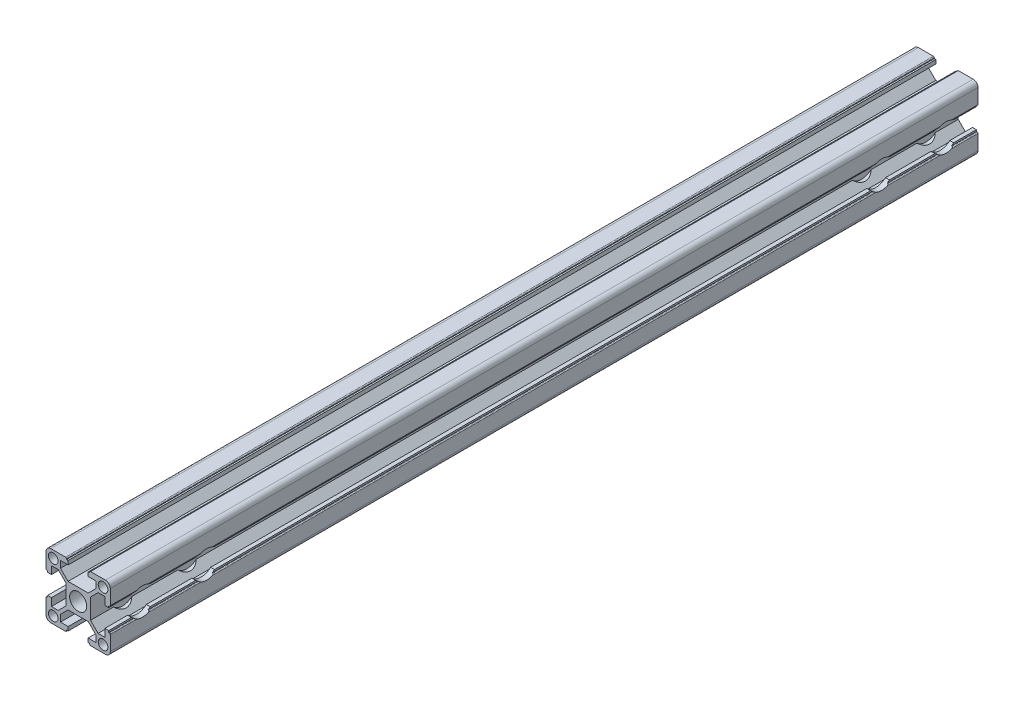
SolidWorks part; units mm, degrees
ref_plane "前视基准面" through (0, 0, 0) normal (0, 0, 1) x (1, 0, 0)
ref_plane "上视基准面" through (0, 0, 0) normal (0, 1, 0) x (1, 0, 0)
ref_plane "右视基准面" through (0, 0, 0) normal (1, 0, 0) x (0, 0, -1)
sketch "草图1" plane through (0, 0, 0) normal (0, 0, 1) x (1, 0, 0)
  line L0 (-7.75, 0) -> (0, 0) construction
  line L1 (7.75, -7.75) -> (-7.75, -7.75) construction
  line L2 (7.75, -7.75) -> (7.75, 7.75) construction
  line L3 (7.75, 7.75) -> (-7.75, 7.75) construction
  line L4 (-7.75, -7.75) -> (-7.75, 7.75) construction
  line L5 (7.75, -7.75) -> (-7.75, 7.75) construction
  line L6 (7.75, 7.75) -> (-7.75, -7.75) construction
  line L7 (0, 0) -> (0, 7.75) construction
  line L8 (3.1429, 3.85) -> (-3.1429, 3.85)
  line L9 (-3.1429, 3.85) -> (-5.5, 6.2071)
  line L10 (-5.5, 6.2071) -> (-5.5, 8.3)
  line L11 (-5.5, 8.3) -> (-3.1, 8.3)
  line L12 (-3.1, 8.3) -> (-3.1, 9.5)
  line L13 (-3.1, 9.5) -> (-3.6, 9.5)
  line L14 (-3.6, 9.5) -> (-3.6, 9.7)
  line L15 (-3.9, 10) -> (-8.5, 10)
  line L16 (-3.85, -3.1429) -> (-3.85, 3.1429)
  line L17 (-3.85, 3.1429) -> (-6.2071, 5.5)
  line L18 (-6.2071, 5.5) -> (-8.3, 5.5)
  line L19 (-8.3, 5.5) -> (-8.3, 3.1)
  line L20 (-9.5, 3.1) -> (-9.5, 3.6)
  line L21 (-8.3, 3.1) -> (-9.5, 3.1)
  line L22 (-9.5, 3.6) -> (-9.7, 3.6)
  line L23 (-10, 3.9) -> (-10, 8.5)
  line L24 (5.5, 8.3) -> (3.1, 8.3)
  line L25 (3.6, 9.5) -> (3.6, 9.7)
  line L26 (3.1, 9.5) -> (3.6, 9.5)
  line L27 (3.1, 8.3) -> (3.1, 9.5)
  line L28 (5.5, 6.2071) -> (5.5, 8.3)
  line L29 (3.1429, 3.85) -> (5.5, 6.2071)
  line L30 (3.85, -3.1429) -> (3.85, 3.1429)
  line L31 (3.85, 3.1429) -> (6.2071, 5.5)
  line L32 (9.5, 3.6) -> (9.7, 3.6)
  line L33 (8.3, 3.1) -> (9.5, 3.1)
  line L34 (9.5, 3.1) -> (9.5, 3.6)
  line L35 (8.3, 5.5) -> (8.3, 3.1)
  line L36 (6.2071, 5.5) -> (8.3, 5.5)
  line L37 (10, 3.9) -> (10, 8.5)
  line L38 (3.9, 10) -> (8.5, 10)
  line L39 (-9.5, -3.6) -> (-9.7, -3.6)
  line L40 (-8.3, -3.1) -> (-9.5, -3.1)
  line L41 (-9.5, -3.1) -> (-9.5, -3.6)
  line L42 (-8.3, -5.5) -> (-8.3, -3.1)
  line L43 (-6.2071, -5.5) -> (-8.3, -5.5)
  line L44 (-3.85, -3.1429) -> (-6.2071, -5.5)
  line L45 (-3.1429, -3.85) -> (-5.5, -6.2071)
  line L46 (-5.5, -6.2071) -> (-5.5, -8.3)
  line L47 (-3.6, -9.5) -> (-3.6, -9.7)
  line L48 (-3.1, -9.5) -> (-3.6, -9.5)
  line L49 (-3.1, -8.3) -> (-3.1, -9.5)
  line L50 (-5.5, -8.3) -> (-3.1, -8.3)
  line L51 (5.5, -6.2071) -> (5.5, -8.3)
  line L52 (3.1, -8.3) -> (3.1, -9.5)
  line L53 (3.1, -9.5) -> (3.6, -9.5)
  line L54 (3.6, -9.5) -> (3.6, -9.7)
  line L55 (5.5, -8.3) -> (3.1, -8.3)
  line L56 (3.1429, -3.85) -> (5.5, -6.2071)
  line L57 (3.1429, -3.85) -> (-3.1429, -3.85)
  line L58 (3.85, -3.1429) -> (6.2071, -5.5)
  line L59 (6.2071, -5.5) -> (8.3, -5.5)
  line L60 (8.3, -5.5) -> (8.3, -3.1)
  line L61 (9.5, -3.1) -> (9.5, -3.6)
  line L62 (8.3, -3.1) -> (9.5, -3.1)
  line L63 (9.5, -3.6) -> (9.7, -3.6)
  line L64 (3.9, -10) -> (8.5, -10)
  line L65 (10, -3.9) -> (10, -8.5)
  line L66 (-10, -3.9) -> (-10, -8.5)
  line L67 (-3.9, -10) -> (-8.5, -10)
  circle A0 centre (0, 0) radius 2.65
  circle A1 centre (-7.75, 7.75) radius 1.5
  circle A2 centre (7.75, 7.75) radius 1.5
  circle A3 centre (7.75, -7.75) radius 1.5
  circle A4 centre (-7.75, -7.75) radius 1.5
  arc A5 (-10, -8.5) -> (-8.5, -10) centre (-8.5, -8.5) ccw
  arc A6 (8.5, -10) -> (10, -8.5) centre (8.5, -8.5) ccw
  arc A7 (10, 8.5) -> (8.5, 10) centre (8.5, 8.5) ccw
  arc A8 (-8.5, 10) -> (-10, 8.5) centre (-8.5, 8.5) ccw
  arc A9 (3.6, -9.7) -> (3.9, -10) centre (3.9, -9.7) ccw
  arc A10 (-3.6, -9.7) -> (-3.9, -10) centre (-3.9, -9.7) cw
  arc A11 (-9.7, -3.6) -> (-10, -3.9) centre (-9.7, -3.9) ccw
  arc A12 (9.7, -3.6) -> (10, -3.9) centre (9.7, -3.9) cw
  arc A13 (9.7, 3.6) -> (10, 3.9) centre (9.7, 3.9) ccw
  arc A14 (-9.7, 3.6) -> (-10, 3.9) centre (-9.7, 3.9) cw
  arc A15 (3.6, 9.7) -> (3.9, 10) centre (3.9, 9.7) cw
  arc A16 (-3.6, 9.7) -> (-3.9, 10) centre (-3.9, 9.7) ccw
  point P46 (0, 3.85)
  point P56 (-3.85, 0)
  point P78 (3.85, 0)
  point P87 (-10, -10)
  point P90 (10, -10)
  point P93 (10, 10)
  point P96 (-10, 10)
  point P99 (3.6, -10)
  point P102 (-3.6, -10)
  point P105 (-10, -3.6)
  point P108 (10, -3.6)
  point P111 (10, 3.6)
  point P114 (-10, 3.6)
  point P117 (3.6, 10)
  point P120 (-3.6, 10)
  dimension "D1" = 5.3
  dimension "D2" = 3
  dimension "D11" = 1.5
  dimension "D12" = 2.25
  dimension "D13" = 0.3
  dimension "D3" = 7.7
  dimension "D4" = 6.2
  dimension "D5" = 1.7
  dimension "D6" = 1.2
  dimension "D7" = 20
  dimension "D8" = 7.2
  dimension "D9" = 11
  dimension "D10" = 1
extrude "凸台-拉伸1" add sketch "草图1" along normal mid plane 270
sketch "草图4" plane through (3.85, 0, 0) normal (1, 0, 0) x (0, 0, -1)
  line L0 (125, 0) -> (-125, 0) construction
  line L1 (-135, -3.1429) -> (-135, 3.1429) construction
  circle A0 centre (-125, 0) radius 2
  circle A1 centre (125, 0) radius 2
  circle A2 centre (-105, 0) radius 2
  circle A3 centre (105, 0) radius 2
  point P4 (0, 0)
  dimension "D1" = 4
  dimension "D2" = 10
  dimension "D3" = 20
  dimension "D4" = 20
extrude "切除-拉伸3" cut sketch "草图4" against normal through all
sketch "草图5" plane through (3.85, 0, 0) normal (1, 0, 0) x (0, 0, -1)
  circle A0 centre (-125, 0) radius 4.25
  circle A1 centre (-105, 0) radius 4.25
  circle A2 centre (105, 0) radius 4.25
  circle A3 centre (125, 0) radius 4.25
  dimension "D1" = 8.5
extrude "切除-拉伸4" cut sketch "草图5" along normal through all
equation "\"D4@草图4\"=\"D3@草图4\""
